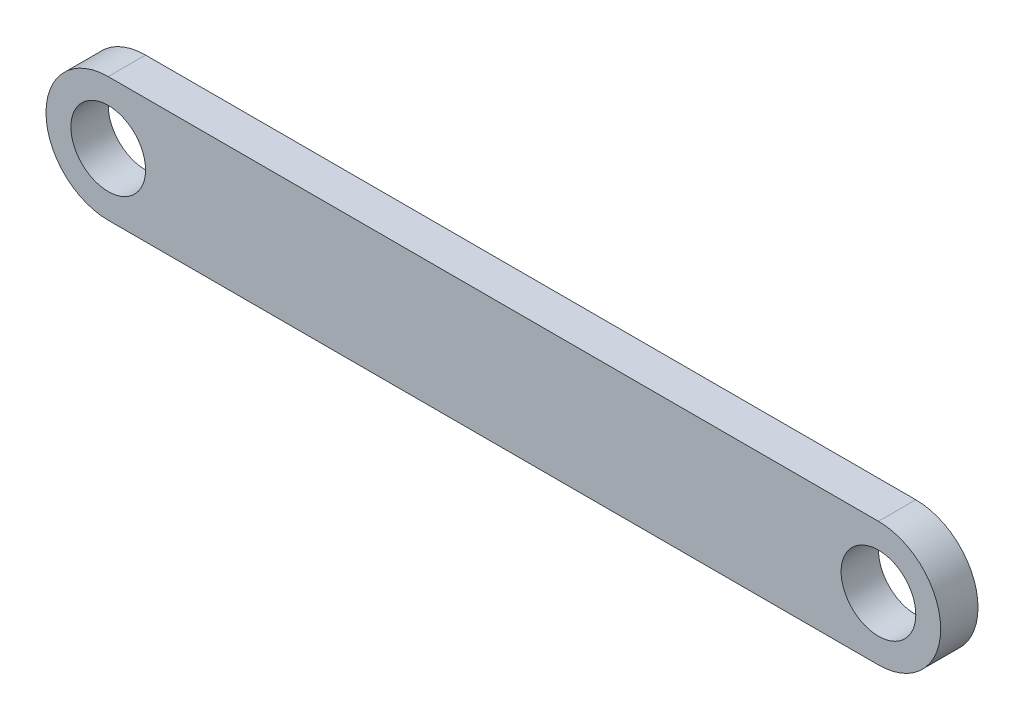
SolidWorks part; units mm, degrees
ref_plane "正面" through (0, 0, 0) normal (0, 0, 1) x (1, 0, 0)
ref_plane "平面" through (0, 0, 0) normal (0, 1, 0) x (1, 0, 0)
ref_plane "右側面" through (0, 0, 0) normal (1, 0, 0) x (0, 0, -1)
sketch "ｽｹｯﾁ1" plane through (0, 0, 0) normal (0, 0, 1) x (1, 0, 0)
  line L0 (-30.95, 0) -> (30.95, 0) construction
  line L1 (-30.95, 5) -> (30.95, 5)
  line L2 (-30.95, -5) -> (30.95, -5)
  arc A0 (-30.95, 5) -> (-30.95, -5) centre (-30.95, 0) ccw
  arc A1 (30.95, -5) -> (30.95, 5) centre (30.95, 0) ccw
  circle A2 centre (-30.95, 0) radius 3
  circle A3 centre (30.95, 0) radius 3
  point P2 (0, 0)
  dimension "D2" = 6
  dimension "D3" = 5
  dimension "D1" = 61.9
extrude "ﾎﾞｽ - 押し出し1" add sketch "ｽｹｯﾁ1" along normal blind 3
